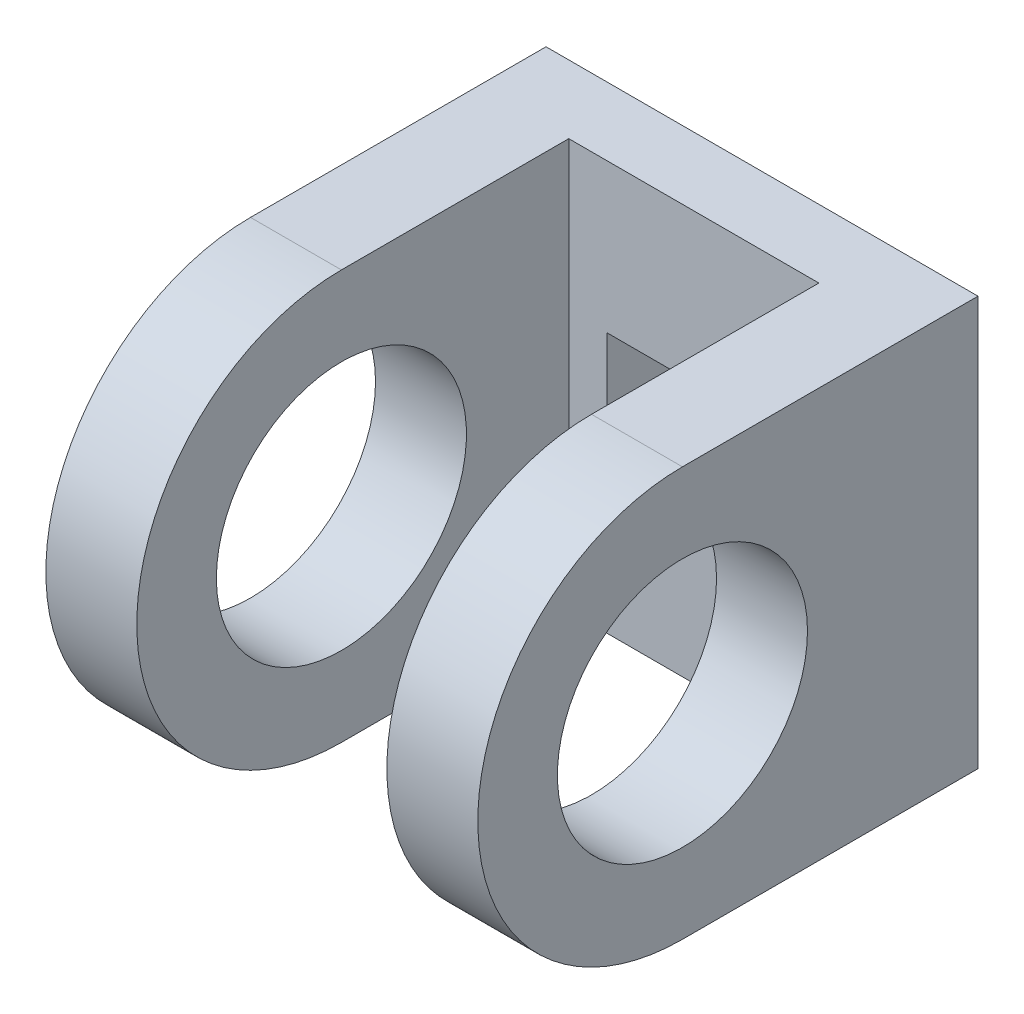
SolidWorks part; units mm, degrees
ref_plane "Front Plane" through (0, 0, 0) normal (0, 0, 1) x (1, 0, 0)
ref_plane "Top Plane" through (0, 0, 0) normal (0, 1, 0) x (1, 0, 0)
ref_plane "Right Plane" through (0, 0, 0) normal (1, 0, 0) x (0, 0, -1)
sketch "Sketch1" plane through (0, 0, 0) normal (1, 0, 0) x (0, 0, -1)
  line L0 (-2, 9) -> (11, 9)
  line L1 (11, 9) -> (11, -9)
  line L2 (11, -9) -> (-2, -9)
  arc A0 (-2, -9) -> (-2, 9) centre (-2, 0) cw
  circle A1 centre (-2, 0) radius 5.5
extrude "Boss-Extrude1" add sketch "Sketch1" along normal blind 19
sketch "Sketch2" plane through (0, 9, 0) normal (0, 1, 0) x (1, 0, 0)
  line L0 (0, -2) -> (4, -2) construction
  line L1 (19, -2) -> (0, -2) construction
  line L2 (19, -2) -> (15, -2) construction
  line L3 (0, -11) -> (19, -11) construction
  line L4 (4, -11) -> (15, -11)
  line L5 (4, -11) -> (4, 8)
  line L6 (4, 8) -> (15, 8)
  line L7 (15, -11) -> (15, 8)
  line L8 (4, -11) -> (15, 8) construction
  line L9 (4, 8) -> (15, -11) construction
  point P12 (9.5, -1.5)
extrude "Cut-Extrude1" cut sketch "Sketch2" against normal blind 33
sketch "Sketch3" plane through (0, 0, -8) normal (0, 0, 1) x (1, 0, 0)
  line L0 (9.5, 9) -> (9.5, -9) construction
  line L1 (15, 9) -> (4, 9) construction
  line L2 (15, -9) -> (4, -9) construction
  line L3 (0, 0) -> (19, 0) construction
  line L4 (19, -9) -> (19, 9) construction
  line L5 (5.6772, 2.4464) -> (13.2754, 2.4464)
  line L6 (5.6772, 2.4464) -> (5.6772, -2.4701)
  line L7 (5.6772, -2.4701) -> (13.2754, -2.4701)
  line L8 (13.2754, 2.4464) -> (13.2754, -2.4701)
  line L9 (5.6772, 2.4464) -> (13.2754, -2.4701) construction
  line L10 (5.6772, -2.4701) -> (13.2754, 2.4464) construction
  point P15 (9.4763, -0.0118)
extrude "Cut-Extrude2" cut sketch "Sketch3" against normal blind 33
